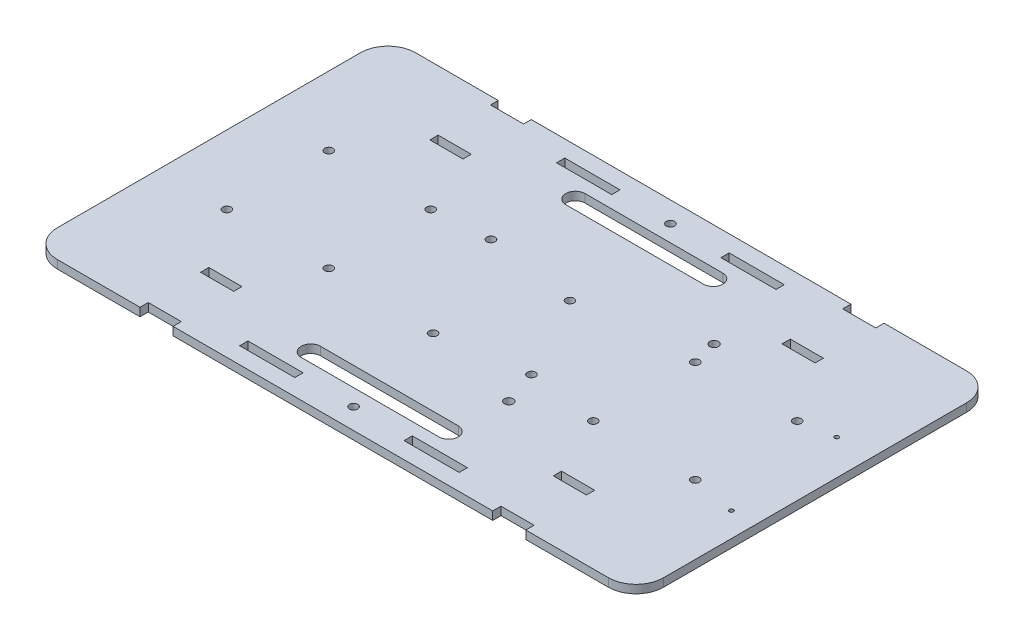
SolidWorks part; units mm, degrees
ref_plane "Front Plane" through (0, 0, 0) normal (0, 0, 1) x (1, 0, 0)
ref_plane "Top Plane" through (0, 0, 0) normal (0, 1, 0) x (1, 0, 0)
ref_plane "Right Plane" through (0, 0, 0) normal (1, 0, 0) x (0, 0, -1)
sketch "Sketch1" plane through (0, 0, 0) normal (0, 1, 0) x (1, 0, 0)
  line L0 (0, 0) -> (0, 23.3747) construction
  line L1 (100, -65) -> (-100, -65)
  line L2 (110, -55) -> (110, 55)
  line L3 (100, 65) -> (-100, 65)
  line L4 (-110, -55) -> (-110, 55)
  line L5 (110, -65) -> (-110, 65) construction
  line L6 (110, 65) -> (-110, -65) construction
  line L11 (0, 0) -> (0, -22.691) construction
  arc A0 (-100, 65) -> (-110, 55) centre (-100, 55) ccw
  arc A1 (-100, -65) -> (-110, -55) centre (-100, -55) cw
  arc A2 (100, -65) -> (110, -55) centre (100, -55) ccw
  arc A3 (110, 55) -> (100, 65) centre (100, 55) ccw
  point P0 (0, 0)
  point P18 (0, 0)
  dimension "D3" = 10
  dimension "D4" = 10
  dimension "D5" = 10
  dimension "D6" = 10
  dimension "D1" = 130
  dimension "D2" = 220
extrude "Boss-Extrude1" add sketch "Sketch1" along normal blind 3
sketch "Sketch2" plane through (0, 3, 0) normal (0, 1, 0) x (1, 0, 0)
  line L0 (70, -65) -> (70, -62)
  line L1 (-100, -65) -> (100, -65) construction
  line L2 (70, -62) -> (58, -62)
  line L3 (58, -62) -> (58, -65)
  line L4 (110, -55) -> (110, 55) construction
  line L5 (58, 65) -> (58, 62)
  line L6 (100, 65) -> (-100, 65) construction
  line L7 (58, 62) -> (70, 62)
  line L8 (70, 62) -> (70, 65)
  line L9 (58, -65) -> (70, -65)
  line L10 (58, 65) -> (70, 65)
  line L11 (-70, -65) -> (-70, -62)
  line L12 (-70, -62) -> (-58, -62)
  line L13 (-58, -62) -> (-58, -65)
  line L14 (-58, -65) -> (-70, -65)
  line L15 (-70, 65) -> (-70, 62.2)
  line L16 (-70, 62.2) -> (-58, 62.2)
  line L17 (-58, 62.2) -> (-58, 65)
  line L18 (-58, 65) -> (-70, 65)
  line L19 (-110, 55) -> (-110, -55) construction
  line L20 (-110, 0) -> (110, 0) construction
  line L21 (-70, 40.2) -> (-58, 40.2)
  line L22 (-70, 40.2) -> (-70, 43.2)
  line L23 (-70, 43.2) -> (-58, 43.2)
  line L24 (-58, 40.2) -> (-58, 43.2)
  line L25 (-70, 40.2) -> (-58, 43.2) construction
  line L26 (-70, 43.2) -> (-58, 40.2) construction
  line L27 (58, 43) -> (70, 43)
  line L28 (58, 43) -> (58, 40)
  line L29 (58, 40) -> (70, 40)
  line L30 (70, 43) -> (70, 40)
  line L31 (58, 43) -> (70, 40) construction
  line L32 (58, 40) -> (70, 43) construction
  line L33 (58, -43) -> (70, -43)
  line L34 (58, -43) -> (58, -40)
  line L35 (58, -40) -> (70, -40)
  line L36 (70, -43) -> (70, -40)
  line L37 (58, -43) -> (70, -40) construction
  line L38 (58, -40) -> (70, -43) construction
  line L39 (-70, -40) -> (-58, -40)
  line L40 (-70, -40) -> (-70, -43)
  line L41 (-70, -43) -> (-58, -43)
  line L42 (-58, -40) -> (-58, -43)
  line L43 (-70, -40) -> (-58, -43) construction
  line L44 (-70, -43) -> (-58, -40) construction
  line L45 (-85, 18.5) -> (-85, -18.5) construction
  line L46 (-85, -18.5) -> (-48, -18.5) construction
  line L47 (-48, -18.5) -> (-48, 18.5) construction
  line L48 (-48, 18.5) -> (-85, 18.5) construction
  line L49 (-58, -62) -> (58, -62) construction
  line L71 (39.8207, -56) -> (19.8207, -56)
  line L72 (-39.8207, -59) -> (-19.8207, -59)
  line L73 (-39.8207, -59) -> (-39.8207, -56)
  line L74 (-39.8207, -56) -> (-19.8207, -56)
  line L75 (-19.8207, -59) -> (-19.8207, -56)
  line L76 (19.8207, -59) -> (19.8207, -56)
  line L77 (39.8207, -59) -> (19.8207, -59)
  line L78 (39.8207, -59) -> (39.8207, -56)
  line L79 (-39.8207, 56) -> (-19.8207, 56)
  line L80 (-19.8207, 59) -> (-19.8207, 56)
  line L81 (-39.8207, 59) -> (-19.8207, 59)
  line L82 (-39.8207, 59) -> (-39.8207, 56)
  line L83 (39.8207, 59) -> (39.8207, 56)
  line L84 (39.8207, 59) -> (19.8207, 59)
  line L85 (19.8207, 59) -> (19.8207, 56)
  line L86 (39.8207, 56) -> (19.8207, 56)
  line L91 (0, 65) -> (0, -65) construction
  circle A0 centre (-85, 18.5) radius 1.5
  circle A1 centre (-48, 18.5) radius 1.5
  circle A2 centre (-85, -18.5) radius 1.5
  circle A3 centre (-48, -18.5) radius 1.5
  circle A4 centre (48, -18.5) radius 1.5
  circle A5 centre (85, -18.5) radius 1.5
  circle A6 centre (48, 18.5) radius 1.5
  circle A7 centre (85, 18.5) radius 1.5
  circle A8 centre (0, -57.5) radius 1.5
  circle A9 centre (0, 57.5) radius 1.5
  point P24 (-64, 41.7)
  point P29 (64, 41.5)
  point P34 (64, -41.5)
  point P39 (-64, -41.5)
  dimension "D29" = 3
  dimension "D30" = 20
  dimension "D10" = 3
  dimension "D1" = 12
  dimension "D2" = 3
  dimension "D3" = 40
  dimension "D4" = 12
  dimension "D5" = 40
  dimension "D6" = 3
  dimension "D7" = 12
  dimension "D8" = 3
  dimension "D9" = 40
  dimension "40" = 40
  dimension "D11" = 12
  dimension "D12" = 3
  dimension "D13" = 3
  dimension "D14" = 12
  dimension "D15" = 19
  dimension "D16" = 19
  dimension "D17" = 3
  dimension "D18" = 12
  dimension "D19" = 12
  dimension "D20" = 3
  dimension "D21" = 12
  dimension "D22" = 3
  dimension "D23" = 19
  dimension "D24" = 19
  dimension "D25" = 25
  dimension "D26" = 18.5
  dimension "D27" = 37
  dimension "D28" = 37
  dimension "D31" = 6
  dimension "D32" = 7.5
extrude "Cut-Extrude1" cut sketch "Sketch2" against normal blind 3
sketch "Sketch4" plane through (0, 3, 0) normal (0, 1, 0) x (1, 0, 0)
  circle A0 centre (26.4682, -27.625) radius 1.6
  circle A1 centre (45.7182, 27.625) radius 1.6
extrude "Cut-Extrude3" cut sketch "Sketch4" against normal blind 3
sketch "Sketch5" plane through (0, 0, 0) normal (0, -1, 0) x (1, 0, 0)
  circle A0 centre (-27.6383, -20) radius 1.5
  circle A1 centre (-8.6383, 20) radius 1.5
  circle A2 centre (22.1639, 15.1) radius 1.475
  circle A3 centre (5.9139, -15.1) radius 1.475
extrude "Cut-Extrude4" cut sketch "Sketch5" against normal blind 3
sketch "Sketch6" plane through (0, 3, 0) normal (0, 1, 0) x (1, 0, 0)
  circle A0 centre (101.2272, -21.5918) radius 0.75
  circle A1 centre (97.2272, 20.6082) radius 0.75
extrude "Cut-Extrude5" cut sketch "Sketch6" against normal blind 3
sketch "Sketch7" plane through (0, 3, 0) normal (0, 1, 0) x (1, 0, 0)
  line L0 (-25, -48) -> (25, -48) construction
  line L1 (-25, -44.5) -> (25, -44.5)
  line L2 (-25, -51.5) -> (25, -51.5)
  line L3 (-58, -65) -> (58, -65) construction
  line L4 (-110, 55) -> (-110, -55) construction
  line L5 (-25, 48) -> (25, 48) construction
  line L6 (-25, 51.5) -> (25, 51.5)
  line L7 (-25, 44.5) -> (25, 44.5)
  line L8 (58, 65) -> (-58, 65) construction
  arc A0 (-25, -44.5) -> (-25, -51.5) centre (-25, -48) ccw
  arc A1 (25, -51.5) -> (25, -44.5) centre (25, -48) ccw
  arc A2 (-25, 51.5) -> (-25, 44.5) centre (-25, 48) ccw
  arc A3 (25, 44.5) -> (25, 51.5) centre (25, 48) ccw
  point P2 (0, -48)
  point P13 (0, 48)
  dimension "D1" = 17
  dimension "D2" = 7
  dimension "D3" = 50
  dimension "D4" = 110
  dimension "D5" = 17
  dimension "D6" = 110
  dimension "D7" = 50
  dimension "D8" = 7
extrude "Cut-Extrude6" cut sketch "Sketch7" against normal blind 3
